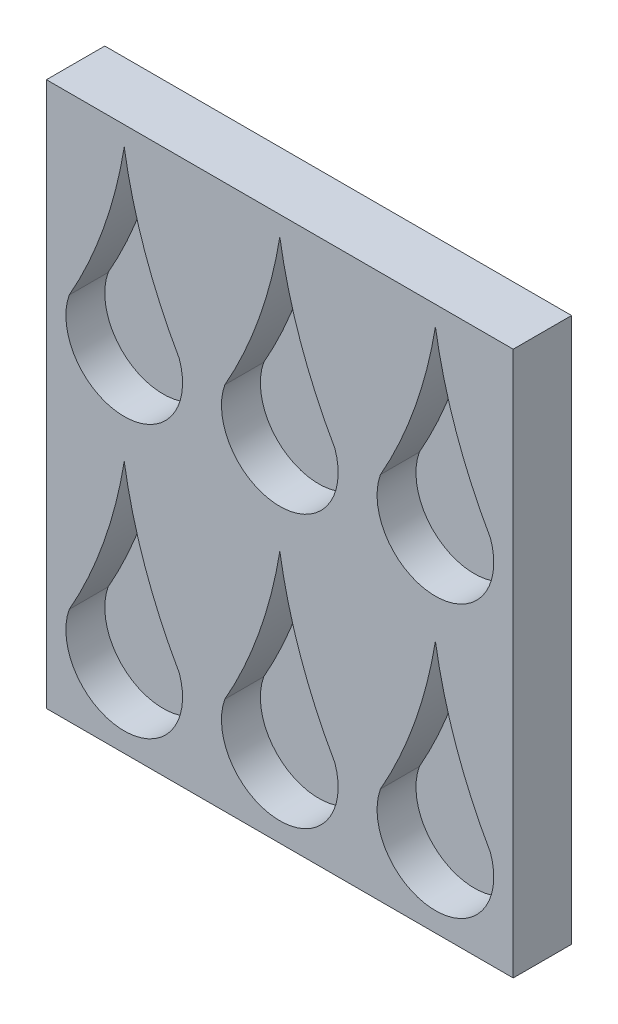
SolidWorks part; units mm, degrees
ref_plane "Front Plane" through (0, 0, 0) normal (0, 0, 1) x (1, 0, 0)
ref_plane "Top Plane" through (0, 0, 0) normal (0, 1, 0) x (1, 0, 0)
ref_plane "Right Plane" through (0, 0, 0) normal (1, 0, 0) x (0, 0, -1)
sketch "Sketch1" plane through (0, 0, 0) normal (0, 0, 1) x (1, 0, 0)
  line L1 (-25.4, -44.45) -> (25.4, -44.45)
  line L2 (-25.4, -44.45) -> (-25.4, 44.45)
  line L3 (-25.4, 44.45) -> (25.4, 44.45)
  line L4 (25.4, -44.45) -> (25.4, 44.45)
  line L5 (-25.4, -44.45) -> (25.4, 44.45) construction
  line L6 (-25.4, 44.45) -> (25.4, -44.45) construction
  point P0 (0, 0)
  dimension "D1" = 50.8
  dimension "D2" = 88.9
extrude "Boss-Extrude1" add sketch "Sketch1" along normal blind 19.05
sketch "Sketch2" plane through (0, 0, 19.05) normal (0, 0, 1) x (1, 0, 0)
  line L1 (0, 0) -> (0, 50000) construction
  line L3 (25.4, 44.45) -> (-25.4, 44.45) construction
  line L4 (-25.4, -44.45) -> (25.4, -44.45) construction
  line L5 (-25.4, 44.45) -> (-25.4, -44.45) construction
  line L6 (-17.9605, -12.7) -> (17.9605, -12.7) construction
  arc A0 (-17.9605, -12.7) -> (17.9605, -12.7) centre (0, -19.05) ccw
  arc A1 (-17.9605, -12.7) -> (0, 38.1) centre (-150.4015, 62.6999) ccw
  arc A2 (17.9605, -12.7) -> (0, 38.1) centre (150.4015, 62.6999) cw
  point P4 (0, 38.1)
  point P12 (-19.05, -19.05)
  point P16 (0, -38.1)
  point P18 (0, 0)
  dimension "D1" = 6.35
  dimension "D5" = 152.4
  dimension "D2" = 6.35
  dimension "D3" = 6.35
  dimension "D4" = 6.35
extrude "Cut-Extrude1" cut sketch "Sketch2" against normal blind 12.7
sketch "Sketch3" plane through (0, 0, 19.05) normal (0, 0, 1) x (1, 0, 0)
  line L0 (0, 0) -> (0, 50000) construction
  line L1 (0, 0) -> (50000, 0) construction
pattern_linear "LPattern1" count 3 spacing 50.8 along (1, 0, 0) count 2 spacing 88.9 along (0, 1, 0) of "Boss-Extrude1", "Cut-Extrude1"
